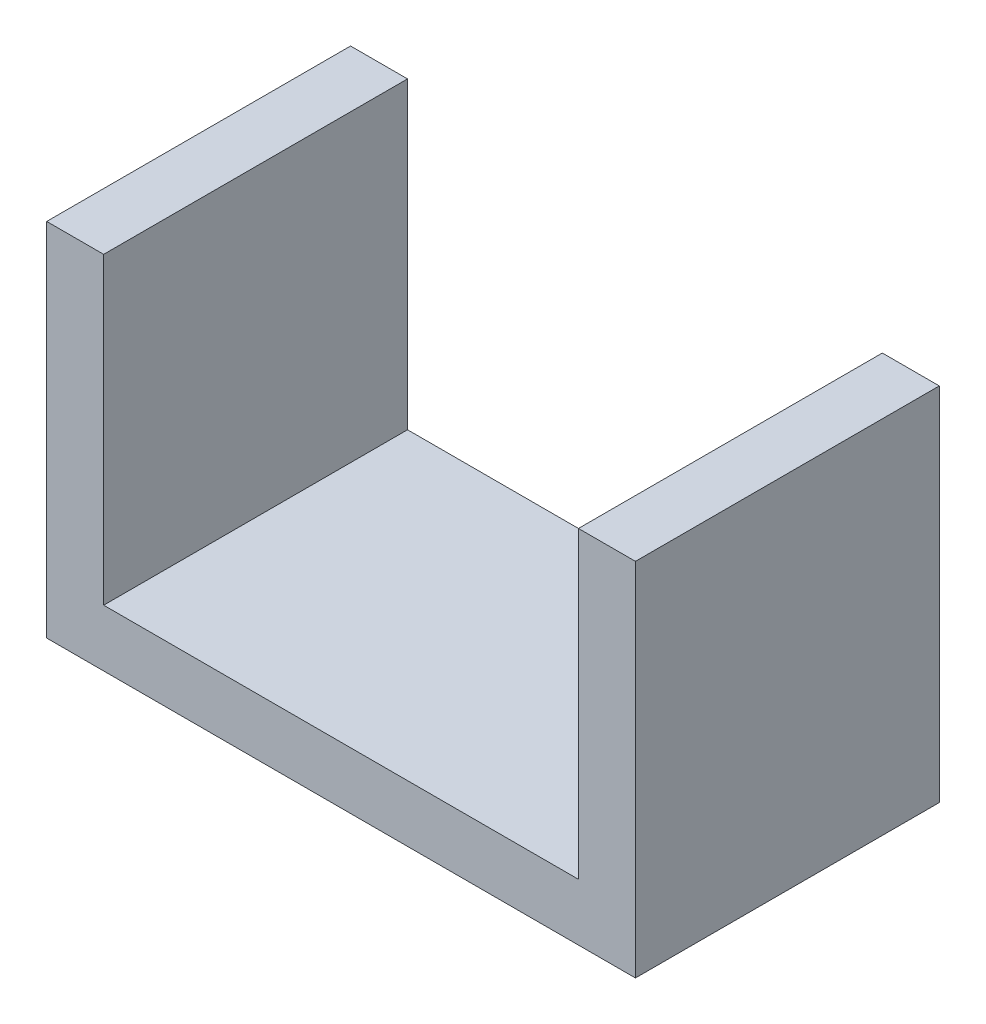
SolidWorks part; units mm, degrees
ref_plane "정면" through (0, 0, 0) normal (0, 0, 1) x (1, 0, 0)
ref_plane "윗면" through (0, 0, 0) normal (0, 1, 0) x (1, 0, 0)
ref_plane "우측면" through (0, 0, 0) normal (1, 0, 0) x (0, 0, -1)
sketch "스케치1" plane through (0, 0, 0) normal (0, 0, 1) x (1, 0, 0)
  line L0 (-9.5788, 5.5678) -> (-9.5788, -3.9322)
  line L1 (-9.5788, -3.9322) -> (5.9212, -3.9322)
  line L2 (5.9212, -3.9322) -> (5.9212, 5.5678)
  line L3 (5.9212, 5.5678) -> (4.4212, 5.5678)
  line L4 (4.4212, 5.5678) -> (4.4212, -2.4322)
  line L5 (4.4212, -2.4322) -> (-8.0788, -2.4322)
  line L6 (-8.0788, -2.4322) -> (-8.0788, 5.5678)
  line L7 (-8.0788, 5.5678) -> (-9.5788, 5.5678)
  dimension "D1" = 12.5
  dimension "D2" = 1.5
  dimension "D3" = 1.5
  dimension "D4" = 1.5
  dimension "D5" = 8
  dimension "D6" = 8
extrude "보스-돌출1" add sketch "스케치1" along normal blind 8
